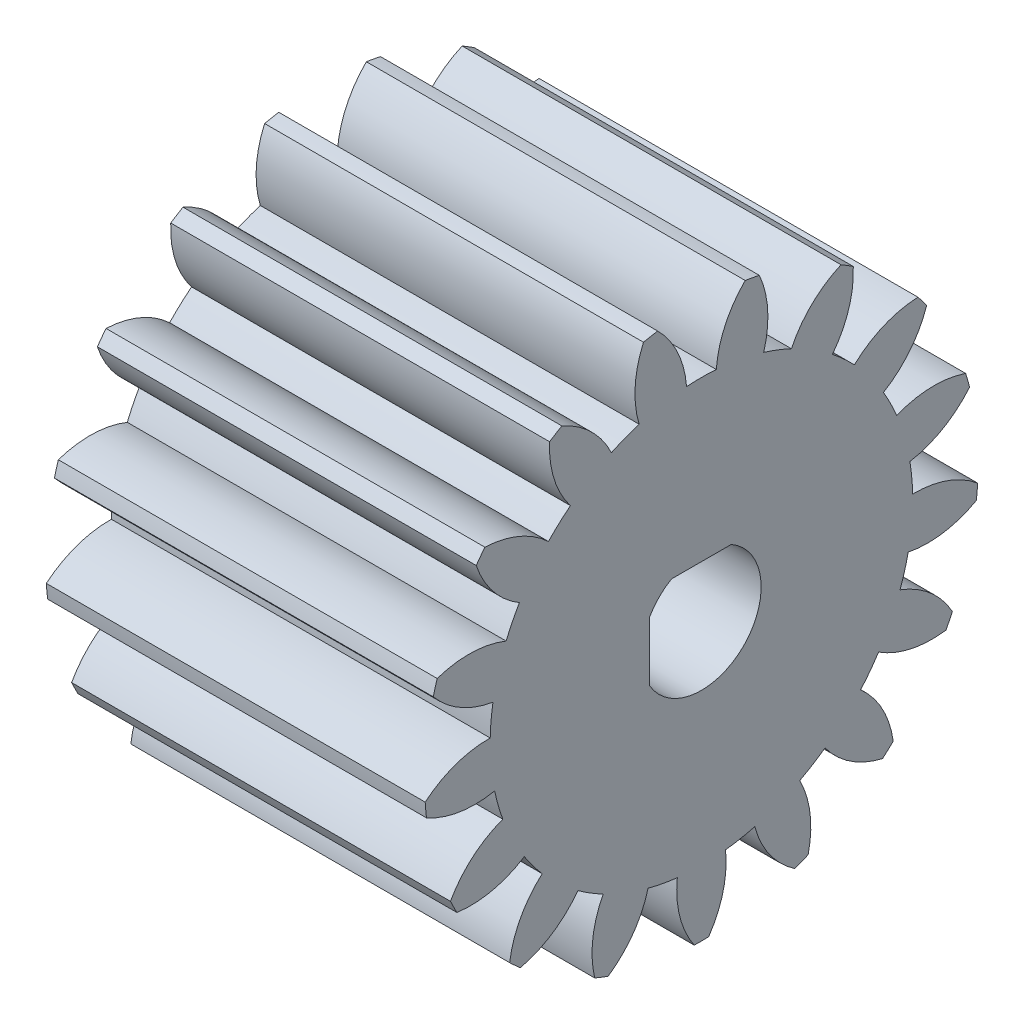
SolidWorks part; units mm, degrees
ref_plane "Plane1" through (0, 0, 0) normal (0, 0, 1) x (1, 0, 0)
ref_plane "Plane2" through (0, 0, 0) normal (0, 1, 0) x (1, 0, 0)
ref_plane "Plane3" through (0, 0, 0) normal (1, 0, 0) x (0, 0, -1)
other "Configuration Table"
sketch "HoldingSke" plane through (0, 0, 0) normal (0, 1, 0) x (1, 0, 0)
  line L0 (0, 0) -> (0.4782, -0.1462)
  line L1 (-15, 0) -> (100, 0) construction
  line L2 (0, 0) -> (-2.1039, 2.3779)
  line L3 (0, 0) -> (-11.863, 4.5341)
  line L4 (0, 0) -> (8.2586, 2.5249)
  line L5 (0, 0) -> (-46.8476, -17.4728)
  line L6 (0, 0) -> (-21.553, -14.5419)
  line L7 (-2.1039, 2.3779) -> (8.6586, 51.2059)
  line L8 (-76.2, 54.61) -> (-74.8, 54.61)
  line L9 (-71.009, 38.7566) -> (-53.1078, 45.2721)
  line L10 (-76.2, 71.12) -> (104.1128, 71.12)
  line L11 (0, 0) -> (-26, 0)
  line L12 (-76.2, 101.6) -> (-76.133, 101.6)
  line L13 (24.9733, 27.94) -> (52.9518, 28.4284)
  line L14 (24.9733, 27.94) -> (24.9743, 27.94)
  line L15 (24.9733, 27.94) -> (100.4006, 29.5858)
  line L16 (-63.627, -2) -> (-12.827, -2)
  circle A0 centre (0, 0) radius 4
  circle A1 centre (0, 0) radius 14.499
  circle A2 centre (0, 0) radius 37.5
  circle A3 centre (0, 0) radius 4
  dimension "MHD" = 28.998
  dimension "Hub_dia" = 75
  dimension "Bore" = 8
  dimension "MBD" = 8
  dimension "Num_teeth" = 17
  dimension "Pitch" = 0.5
  dimension "Overall_len" = 50
  dimension "Show_teeth" = 17
  dimension "Thickness" = 26
  dimension "OAL" = 50.0001
  dimension "T_dim" = 1.4
  dimension "Ap" = 20
  dimension "H" = 19.05
  dimension "Pitch_radius" = 180.3128
  dimension "Width" = 26
  dimension "Backlash" = 0.067
  dimension "Addendum_fac" = 1
  dimension "Dedendum_fac" = 1.25
  dimension "Clearance_fac" = 0.25
  dimension "Dedendum_add" = 0.001
  dimension "Module" = 2
sketch "BasProSke" plane through (0, 0, 0) normal (0, 1, 0) x (1, 0, 0)
  line L0 (-10, 0) -> (60, 0) construction
  line L1 (0, 0) -> (0, 19)
  line L2 (0, 0) -> (26, 0)
  line L3 (26, 0) -> (26, 19)
  line L4 (26, 19) -> (0, 19)
  dimension "Thickness" = 26
  dimension "Diameter" = 38
revolve "Base-Revolve" add sketch "BasProSke" angle 360 about L0
sketch "TooCutSke" plane through (0, 0, 0) normal (1, 0, 0) x (0, 0, -1)
  line L1 (0, 0) -> (0, 107) construction
  line L2 (0, 0) -> (-1.6857, 16.9162) construction
  line L3 (0, 0) -> (-6.2247, 33.2991) construction
  line L4 (-1.6857, 16.9162) -> (-3.1123, 16.6495) construction
  arc A0 (1.0204, 14.4631) -> (-1.0204, 14.4631) centre (0, 0) ccw
  arc A1 (3.0261, 18.7832) -> (-3.0261, 18.7832) centre (0, 0) ccw
  circle A2 centre (0, 0) radius 17 construction
  circle A3 centre (0, 0) radius 15.9748 construction
  arc A4 (-1.0204, 14.4631) -> (-3.0261, 18.7832) centre (-7.8003, 13.9409) ccw
  arc A5 (3.0261, 18.7832) -> (1.0204, 14.4631) centre (7.8003, 13.9409) ccw
  dimension "Root_dia" = 28.998
  dimension "Overcut_dia" = 38.0508
  dimension "Pitch_dia" = 34
  dimension "Base_dia" = 31.9495
  dimension "Flank_rad" = 6.8
  dimension "Half_ang" = 10.588
  dimension "Half_CT" = 1.4513
extrude "ToothCut" cut sketch "TooCutSke" along normal through all
fillet "Breaks" [suppressed] radius 0.04
fillet "RootFillets" [suppressed] radius 0.501
pattern_circular "TeethCuts" count 17 every 21.176 about axis through (-10, 0, 0) along (1, 0, 0) of "ToothCut", "RootFillets", "Breaks"
sketch "HubNeaOneSke" plane through (0, 0, 0) normal (-1, 0, 0) x (0, 0, 1)
  circle A0 centre (0, 0) radius 14.499
  dimension "Diameter" = 28.998
extrude "HubNearOne" [suppressed] add sketch "HubNeaOneSke" along normal blind 24.0001
sketch "HubNeaBotSke" plane through (0, 0, 0) normal (-1, 0, 0) x (0, 0, 1)
  circle A0 centre (0, 0) radius 14.499
  dimension "Diameter" = 28.998
extrude "HubNearBoth" [suppressed] add sketch "HubNeaBotSke" along normal blind 12
ref_plane "FarPln" through (26, 0, 0) normal (1, 0, 0) x (0, 0, -1)
sketch "HubFarSke" plane through (26, 0, 0) normal (1, 0, 0) x (0, 0, -1)
  circle A0 centre (0, 0) radius 14.499
  dimension "Diameter" = 28.998
extrude "HubFar" [suppressed] add sketch "HubFarSke" along normal blind 12
sketch "BorSke" plane through (0, 0, 0) normal (1, 0, 0) x (0, 0, -1)
  line L0 (-3.55, 2.0512) -> (-3.55, -2.0512)
  line L1 (2.0512, 3.55) -> (-2.0512, 3.55)
  arc A0 (-3.55, -2.0512) -> (2.0512, 3.55) centre (0, 0) ccw
  arc A1 (-2.0512, 3.55) -> (-3.55, 2.0512) centre (0, 0) ccw
  dimension "D1" = 8.2
  dimension "D2" = 3.55
  dimension "D3" = 3.55
extrude "Bore" cut sketch "BorSke" along normal mid plane 100.0001
sketch "KeySke" plane through (0, 0, 0) normal (1, 0, 0) x (0, 0, -1)
  line L0 (-1.5, 0) -> (-1.5, 5.4)
  line L1 (-1.5, 5.4) -> (1.5, 5.4)
  line L2 (1.5, 5.4) -> (1.5, 0)
  line L3 (0, 0) -> (0, 34) construction
  line L4 (-1.5, 0) -> (1.5, 0)
  dimension "Offset" = 5.4
  dimension "Width" = 3
extrude "Keyway" [suppressed] cut sketch "KeySke" along normal mid plane 100.0001
pattern_circular "Keyway2" [suppressed] count 2 every 90 about axis through (-10, 0, 0) along (1, 0, 0)
equation "' \"Module@HoldingSke\" = 6.35"
equation "' \"Num_teeth@HoldingSke\" = 12"
equation "' \"Ap@HoldingSke\" =  20"
equation "' \"Ap@HoldingSke\" = 20"
equation "' \"Width@HoldingSke\" = 0.5 * 25.4"
equation "' \"Hub_dia@HoldingSke\"= 1 * 25.4"
equation "' \"Hub_dia@HoldingSke\" = 1 * 25.4"
equation "' \"Overall_len@HoldingSke\" = 1.0 * 25.4"
equation "' \"Bore@HoldingSke\" = 0.75 * 25.4"
equation "' \"T_dim@HoldingSke\" = 0.1 * 25.4"
equation "' \"Width@KeySke\" = 0.25 * 25.4"
equation "' \"Show_teeth@HoldingSke\" = 13"
equation "' \"Backlash@HoldingSke\" = 0.009 * 25.4"
equation "' \"Addendum_fac@HoldingSke\" = 1.0"
equation "' \"Dedendum_fac@HoldingSke\" = 1.25"
equation "' \"Dedendum_add@HoldingSke\" = 0.00005 * 25.4"
equation "' \"Clearance_fac@HoldingSke\" = 0.25"
equation "\"Pitch@HoldingSke\" = 1 / \"Module@HoldingSke\""
equation "\"Overcut_dia@TooCutSke\" = (\"Num_teeth@HoldingSke\" + 2 * \"Addendum_fac@HoldingSke\") / \"Pitch@HoldingSke\" + 0.002 * 25.4"
equation "\"Pitch_dia@TooCutSke\" = \"Num_teeth@HoldingSke\" / \"Pitch@HoldingSke\""
equation "\"Base_dia@TooCutSke\" = \"Num_teeth@HoldingSke\" / \"Pitch@HoldingSke\" * cos((\"Ap@HoldingSke\"  * 3.14159265 / 180))"
equation "\"Root_dia@TooCutSke\" = (\"Num_teeth@HoldingSke\" + 2) / \"Pitch@HoldingSke\" - 2 * (\"Addendum_fac@HoldingSke\" + \"Dedendum_fac@HoldingSke\") / \"Pitch@HoldingSke\" - \"Dedendum_add@HoldingSke\" * 2"
equation "\"Half_ang@TooCutSke\" = 180 / \"Num_teeth@HoldingSke\""
equation "\"Half_CT@TooCutSke\" = \"Num_teeth@HoldingSke\" / \"Pitch@HoldingSke\" * sin((3.14159265 / 2 / \"Num_teeth@HoldingSke\")) / 2 - 7 * \"Backlash@HoldingSke\" / 4"
equation "\"Flank_rad@TooCutSke\" = \"Num_teeth@HoldingSke\" / \"Pitch@HoldingSke\" / 5"
equation "\"Radius@RootFillets\" = \"Clearance_fac@HoldingSke\" / \"Pitch@HoldingSke\" + \"Dedendum_add@HoldingSke\""
equation "\"Break_rad@Breaks\" = 0.02 / \"Pitch@HoldingSke\""
equation "\"Thickness@HoldingSke\" = \"Width@HoldingSke\""
equation "\"OAL@HoldingSke\" = \"Thickness@HoldingSke\""
equation "\"MHD@HoldingSke\" = (\"Num_teeth@HoldingSke\" + 2) / \"Pitch@HoldingSke\" - 2 * (\"Addendum_fac@HoldingSke\" + \"Dedendum_fac@HoldingSke\")  / \"Pitch@HoldingSke\" - \"Dedendum_add@HoldingSke\" * 2"
equation "\"MBD@HoldingSke\" = (\"Num_teeth@HoldingSke\" + 2) / \"Pitch@HoldingSke\" - 2 * (\"Addendum_fac@HoldingSke\" + \"Dedendum_fac@HoldingSke\")  / \"Pitch@HoldingSke\" - \"Dedendum_add@HoldingSke\" * 2 - 0.002 * 25.4"
equation "\"MHD@HoldingSke\" = ((sgn( \"MHD@HoldingSke\" - \"Hub_dia@HoldingSke\" )-1)*( \"MHD@HoldingSke\" - \"Hub_dia@HoldingSke\" ))/-2+ \"Hub_dia@HoldingSke\""
equation "\"MBD@HoldingSke\" = ((sgn( \"MBD@HoldingSke\" - \"Bore@HoldingSke\" )-1)*( \"MBD@HoldingSke\" - \"Bore@HoldingSke\" ))/-2+ \"Bore@HoldingSke\""
equation "\"OAL@HoldingSke\" = ((sgn( \"OAL@HoldingSke\" - \"Overall_len@HoldingSke\" )+1)*( \"OAL@HoldingSke\" - \"Overall_len@HoldingSke\" ))/2 + \"Overall_len@HoldingSke\" + 0.000002 * 25.4"
equation "\"Num_teeth@TeethCuts\" = int( \"Show_teeth@HoldingSke\" ) + 1"
equation "\"Num_teeth@TeethCuts\" = ((sgn( \"Num_teeth@TeethCuts\" - \"Num_teeth@HoldingSke\" )-1)*( \"Num_teeth@TeethCuts\" - \"Num_teeth@HoldingSke\" ))/-2+ \"Num_teeth@HoldingSke\""
equation "\"Num_teeth@TeethCuts\" = ((sgn( \"Num_teeth@TeethCuts\" - 2.0)+1)*( \"Num_teeth@TeethCuts\" - 2.0))/2 +2.0"
equation "\"Angle@TeethCuts\" = 360.0 / \"Num_teeth@HoldingSke\""
equation "\"Diameter@BasProSke\" = (\"Num_teeth@HoldingSke\" + 2 * \"Addendum_fac@HoldingSke\") / \"Pitch@HoldingSke\""
equation "\"Thickness@BasProSke\"  = \"Thickness@HoldingSke\""
equation "' \"Fillet_rad@BasProSke\" =  \"Thickness@HoldingSke\" * 0.05"
equation "' \"Fillet_rad@BasProSke\" = \"Thickness@HoldingSke\" * 0.05"
equation "\"MHD@HoldingSke\" = ((sgn( \"MHD@HoldingSke\" - \"Root_dia@TooCutSke\" )-1)*( \"MHD@HoldingSke\" - \"Root_dia@TooCutSke\" ))/-2+ \"Root_dia@TooCutSke\""
equation "\"Diameter@HubNeaOneSke\" = \"MHD@HoldingSke\""
equation "\"Length@HubNearOne\" = \"OAL@HoldingSke\" - \"Thickness@BasProSke\""
equation "\"Diameter@HubNeaBotSke\" = \"MHD@HoldingSke\""
equation "\"Length@HubNearBoth\" = ( \"OAL@HoldingSke\" - \"Thickness@BasProSke\" ) / 2.0"
equation "\"Thickness@FarPln\" = \"Thickness@BasProSke\""
equation "\"Diameter@HubFarSke\" = \"MHD@HoldingSke\""
equation "\"Length@HubFar\" = ( \"OAL@HoldingSke\" - \"Thickness@BasProSke\" ) / 2.0"
equation "\"D1@Bore\" = \"OAL@HoldingSke\" * 2.0"
equation "\"D1@Keyway\" = \"OAL@HoldingSke\" * 2.0"
equation "\"Offset@KeySke\" = \"T_dim@HoldingSke\" + \"MBD@HoldingSke\" / 2.0"
